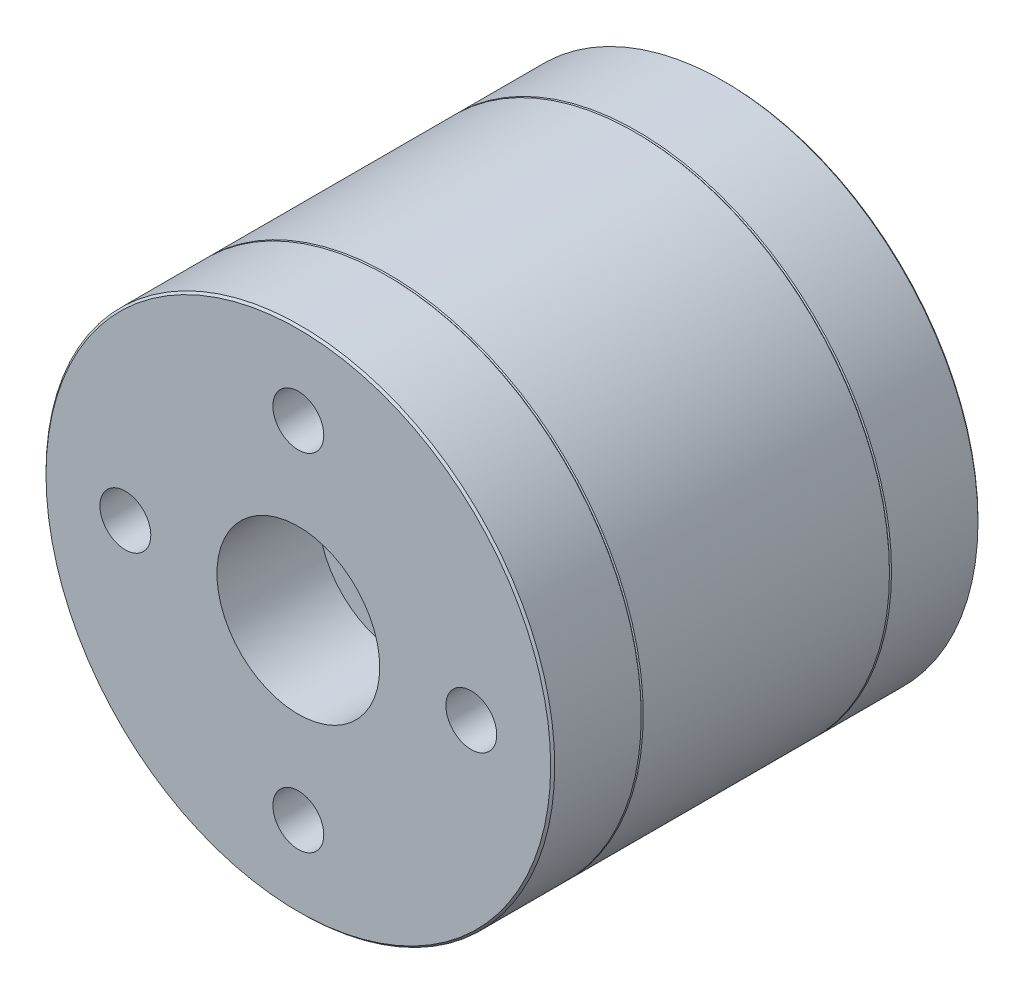
SolidWorks part; units mm, degrees
ref_plane "Front Plane" through (0, 0, 0) normal (0, 0, 1) x (1, 0, 0)
ref_plane "Top Plane" through (0, 0, 0) normal (0, 1, 0) x (1, 0, 0)
ref_plane "Right Plane" through (0, 0, 0) normal (1, 0, 0) x (0, 0, -1)
sketch "Sketch1" plane through (0, 0, 0) normal (0, 0, 1) x (1, 0, 0)
  circle A0 centre (0, 0) radius 12.5
  dimension "D1" = 25
extrude "Boss-Extrude1" add sketch "Sketch1" along normal mid plane 21
ref_axis "Axis1" through (0, 0, 10.5) along (0, 0, -1)
sketch "Sketch2" plane through (0, 0, 0) normal (1, 0, 0) x (0, 0, -1)
  line L0 (-6.15, 12.5) -> (-6.05, 12.5)
  line L1 (10.5, 12.5) -> (-10.5, 12.5) construction
  line L2 (-6.05, 12.5) -> (-6.1, 12.45)
  line L3 (-6.1, 12.45) -> (-6.15, 12.5)
  line L4 (6.05, 12.5) -> (6.15, 12.5)
  line L5 (6.15, 12.5) -> (6.1, 12.45)
  line L6 (6.1, 12.45) -> (6.05, 12.5)
  line L7 (10.5, -12.5) -> (10.5, 12.5) construction
  line L8 (-10.5, 12.5) -> (-10.5, -12.5) construction
  dimension "D1" = 0.1
  dimension "D2" = 4.4
  dimension "D3" = 4.4
revolve "Cut-Revolve1" cut sketch "Sketch2" angle 360 about axis through (0, 0, 10.5) along (0, 0, -1)
chamfer "Chamfer1" distance 0.1 angle 45 2 edges at (12.5, 0, -10.5) (12.5, 0, 10.5)
sketch "Sketch4" plane through (0, 0, -10.5) normal (0, 0, -1) x (-1, 0, 0)
  circle A0 centre (0, 0) radius 3.51
  dimension "D1" = 7.02
extrude "Cut-Extrude1" cut sketch "Sketch4" against normal blind 1
sketch "Sketch5" plane through (0, 0, -9.5) normal (0, 0, -1) x (-1, 0, 0)
  circle A0 centre (0, 0) radius 3.5
  dimension "D1" = 7
extrude "Boss-Extrude2" add sketch "Sketch5" along normal blind 3.5
sketch "Sketch6" plane through (0, 0, -13) normal (0, 0, -1) x (-1, 0, 0)
  circle A0 centre (0, 0) radius 2
  dimension "D1" = 4
extrude "Cut-Extrude2" cut sketch "Sketch6" against normal up to next
sketch "Sketch7" plane through (0, 0, 10.5) normal (0, 0, 1) x (1, 0, 0)
  circle A0 centre (0, 0) radius 4
  dimension "D1" = 8
extrude "Cut-Extrude3" cut sketch "Sketch7" against normal blind 5
chamfer "Chamfer2" distance 0.2 angle 45 2 edges at (-3.5, 0, -13) (-2, 0, -13)
sketch "Sketch8" plane through (0, 0, -10.5) normal (0, 0, -1) x (-1, 0, 0)
  circle A0 centre (0, 8.5) radius 1.25
  circle A1 centre (8.5, 0) radius 1.25
  circle A2 centre (0, -8.5) radius 1.25
  circle A3 centre (-8.5, 0) radius 1.25
  point P12 (0, 0)
  dimension "D2" = 2.5
  dimension "D1" = 8.5
  dimension "D3" = 4
extrude "Cut-Extrude4" cut sketch "Sketch8" against normal up to next
cosmetic thread "Cosmetic Thread11" parameters "D2"=3
cosmetic thread "Cosmetic Thread12" parameters "D2"=3
sketch "Sketch9" plane through (0, 0, -10.5) normal (0, 0, -1) x (-1, 0, 0)
  circle A0 centre (-8.5, 0) radius 2.5
  circle A1 centre (8.5, 0) radius 2.5
  dimension "D1" = 5
extrude "Cut-Extrude5" cut sketch "Sketch9" against normal blind 3
chamfer "Chamfer3" distance 0.25 angle 45 2 edges at (-11, 0, -10.5) (6, 0, -10.5)
